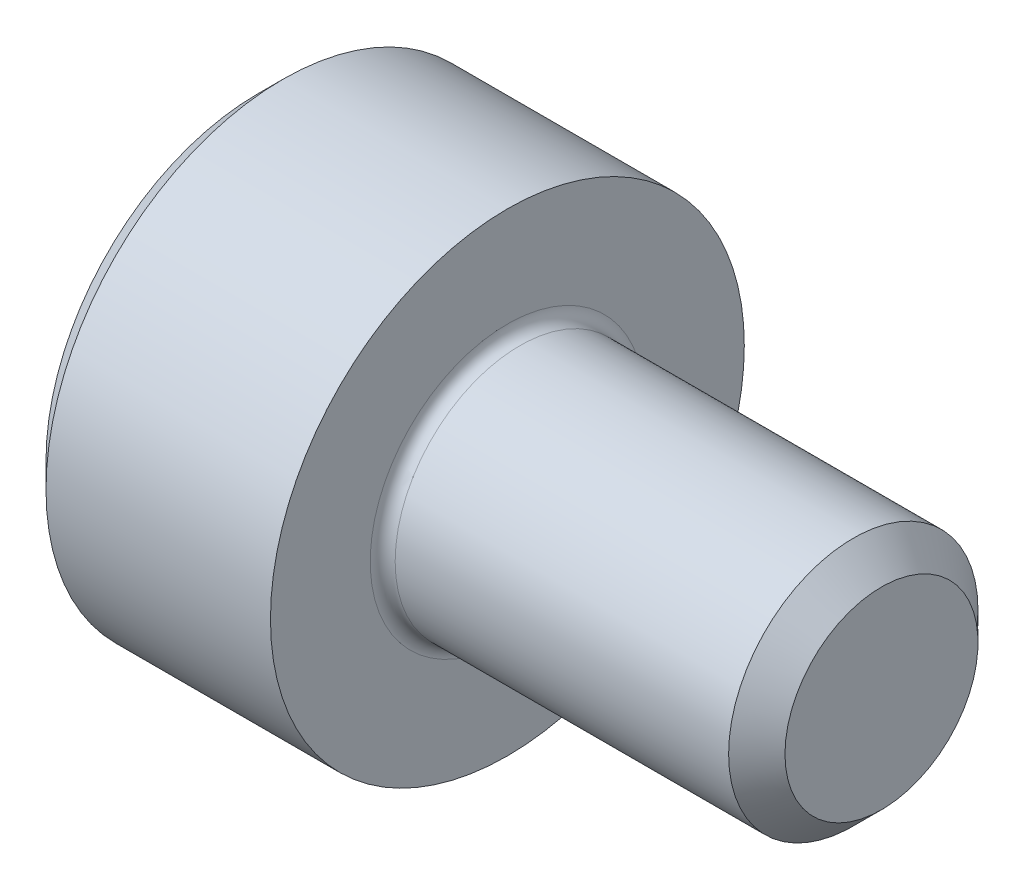
SolidWorks part; units mm, degrees
revolve "Base-Revolve" add sketch "BodySke"
sketch "BodySke" plane through (0, 0, 0) normal (0, 0, 1) x (1, 0, 0)
  line L0 (0, 0) -> (0, 1.7)
  line L1 (0.2, 1.9) -> (2, 1.9)
  line L2 (2, 1.9) -> (2, 1)
  line L3 (2, 1) -> (4.774, 1)
  line L4 (5, 0.774) -> (5, 0)
  line L5 (5, 0) -> (0, 0)
  line L6 (-31.75, 0) -> (127, 0) construction
  line L7 (0, 1.7) -> (0.2, 1.9)
  line L8 (5, 0.774) -> (4.774, 1)
  line L9 (0, -1.7) -> (0.2, -1.9) construction
  line L10 (5, -0.774) -> (4.774, -1) construction
  line L11 (2.4, 9.525) -> (2.4, 3.175) construction
  line L12 (2, 9.525) -> (2, 3.175) construction
  line L13 (-45, 9.525) -> (-45, 3.175) construction
  dimension "Diameter" = 2
  dimension "Head_ht" = 2
  dimension "Length" = 3
  dimension "Body_ch_ang" = 45
  dimension "Head_dia" = 3.8
  dimension "Head_ch_ang" = 45
  dimension "Minor_dia" = 1.548
  dimension "Advance" = 0.4
  dimension "Thread_nom" = 3
  dimension "Thread_length" = 50
  dimension "Head_ch_ht" = 0.2
cosmetic thread "ThreadCosmetic" [suppressed]
fillet "Fillet1" radius 0.1 1 edges at (2, 0, 1)
ref_plane "Plane1" through (0, 0, 0) normal (0, 0, 1) x (1, 0, 0)
ref_plane "Plane2" through (0, 0, 0) normal (0, 1, 0) x (1, 0, 0)
ref_plane "Plane3" through (0, 0, 0) normal (1, 0, 0) x (0, 0, -1)
sketch "Sketch2" plane through (0, 0, 0) normal (0, 0, 1) x (1, 0, 0)
  line L0 (0, 0.7725) -> (1, 0.7725)
  line L1 (1, 0.7725) -> (1.446, 0)
  line L2 (-31.75, 0) -> (127, 0) construction
  line L3 (1.446, 0) -> (0, 0)
  line L4 (0, 0) -> (0, 0.7725)
  line L5 (0, 1.7) -> (0, -1.7) construction
  line L6 (0, 0) -> (47.625, 0) construction
  line L7 (2, -1.9) -> (2, 1.9) construction
  dimension "D1" = 0.7725
  dimension "D2" = 60
revolve "Hex-PreBroach" cut sketch "Sketch2" angle 360 about L6
sketch "Sketch3" plane through (0, 0, 0) normal (-1, 0, 0) x (0, 0.5, 0.866)
  line L0 (0.446, 0.7725) -> (-0.446, 0.7725)
  line L1 (-0.446, 0.7725) -> (-0.892, 0)
  line L2 (0.446, 0.7725) -> (0.892, 0)
  line L3 (0.446, -0.7725) -> (0.892, 0)
  line L4 (0.446, -0.7725) -> (-0.446, -0.7725)
  line L5 (-0.446, -0.7725) -> (-0.892, 0)
  dimension "D1" = 0.7725
  dimension "D2" = 0.7725
  dimension "Hex_size" = 1.545
extrude "Hex" cut sketch "Sketch3" against normal blind 1
sketch "Sketch4" plane through (0, 0, 0) normal (-1, 0, 0) x (0, 0, 1)
  line L0 (0, 0) -> (0.9398, 0)
  line L1 (0, 0) -> (6.1484, 3.5498) construction
  line L2 (0, 0) -> (0.4699, 0.8139)
  line L3 (0.7832, 0.2175) -> (0.8962, 0.2828)
  line L4 (0.58, 0.5695) -> (0.693, 0.6348)
  arc A0 (0.7832, 0.2175) -> (0.58, 0.5695) centre (0, 0) ccw
  arc A1 (0.9398, 0) -> (0.8962, 0.2828) centre (0, 0) ccw
  arc A2 (0.4699, 0.8139) -> (0.693, 0.6348) centre (0, 0) cw
  dimension "D1" = 30
  dimension "D2" = 60
  dimension "Spline_p_dim" = 0.4064
  dimension "D3" = 0.2032
extrude "Spline" [suppressed] cut sketch "Sketch4" against normal blind 1
pattern_circular "CirPattern1" [suppressed] count 6 every 60
sketch "Sketch5" plane through (0, 0, 0) normal (0, 0, 1) x (1, 0, 0)
  line L0 (-31.75, 0) -> (127, 0) construction
  line L2 (0, 1.7) -> (0, -1.7) construction
  circle A0 centre (0.1, 0) radius 0.005
  dimension "Drilled_hole_dia" = 0.01
  dimension "Drilled_hole_loc" = 0.1
extrude "Hole" [suppressed] cut sketch "Sketch5" against normal through all and the other way through all
pattern_circular "Drilled-4" [suppressed] count 2 every 60
pattern_circular "Drilled-6" [suppressed] count 3 every 60
sketch "ThdSchSke" plane through (0, 0, 0) normal (0, 0, 1) x (1, 0, 0)
  line L0 (2.4, -0.774) -> (2.2418, -1)
  line L1 (2.4, -0.774) -> (2.5582, -1)
  line L2 (2.5582, -1) -> (2.5582, -1.25)
  line L3 (-3.175, 0) -> (5.1513, 0) construction
  line L5 (2.5582, -1.25) -> (2.2418, -1.25)
  line L6 (2.2418, -1.25) -> (2.2418, -1)
  line L7 (0, 1.7) -> (0, -1.7) construction
  dimension "Thread_minor" = 1.548
  dimension "Diameter" = 2
  dimension "Start" = 2.4
revolve "ThreadSchematic" [suppressed] cut sketch "ThdSchSke" angle 360 about L3
pattern_linear "ThdSchPat" [suppressed]
equation "\"D2@Sketch3\" = \"Hex_size@Sketch3\" / 2"
equation "\"D1@Sketch3\" = \"Hex_size@Sketch3\" / 2"
equation "\"D1@Sketch2\" = \"Hex_size@Sketch3\" / 2"
equation "\"D3@Sketch4\" = \"Spline_p_dim@Sketch4\" / 2"
equation "\"Thread_minor@ThreadCosmetic\"  =  \"Minor_dia@BodySke\""
equation "\"D2@CirPattern1\" = 360 / \"Num_teeth@CirPattern1\""
equation "\"Wall_thickness@Sketch2\" = \"Head_ht@BodySke\" - \"Key_eng@Hex\""
equation "\"Thread_length@ThreadCosmetic\" = ((sgn( (\"Length@BodySke\" - \"Advance@BodySke\" ) - \"Thread_nom@BodySke\" )-1)*( (\"Length@BodySke\" - \"Advance@BodySke\" ) - \"Thread_nom@BodySke\" ))/-2+ \"Thread_nom@BodySke\""
equation "\"Thread_minor@ThdSchSke\" = \"Minor_dia@BodySke\""
equation "\"Diameter@ThdSchSke\" = \"Diameter@BodySke\""
equation "\"Overcut@ThdSchSke\" = \"Diameter@BodySke\" * 1.25"
equation "\"Start@ThdSchSke\" = \"Head_ht@BodySke\" + \"Length@BodySke\" - \"Thread_length@ThreadCosmetic\"  '---Non-countersunk---"
equation "\"Num_threads@ThdSchPat\" = int( \"Thread_length@ThreadCosmetic\" / \"Advance@BodySke\" + 0.999 )  + 1"
equation "\"Advance@ThdSchPat\" = \"Thread_length@ThreadCosmetic\" /  (\"Num_threads@ThdSchPat\" - 1) 'relax it"
equation "\"Num_threads@ThdSchPat\" = \"Num_threads@ThdSchPat\" - sgn( \"Num_threads@ThdSchPat\" - 1) '---chamfered tips only---"
